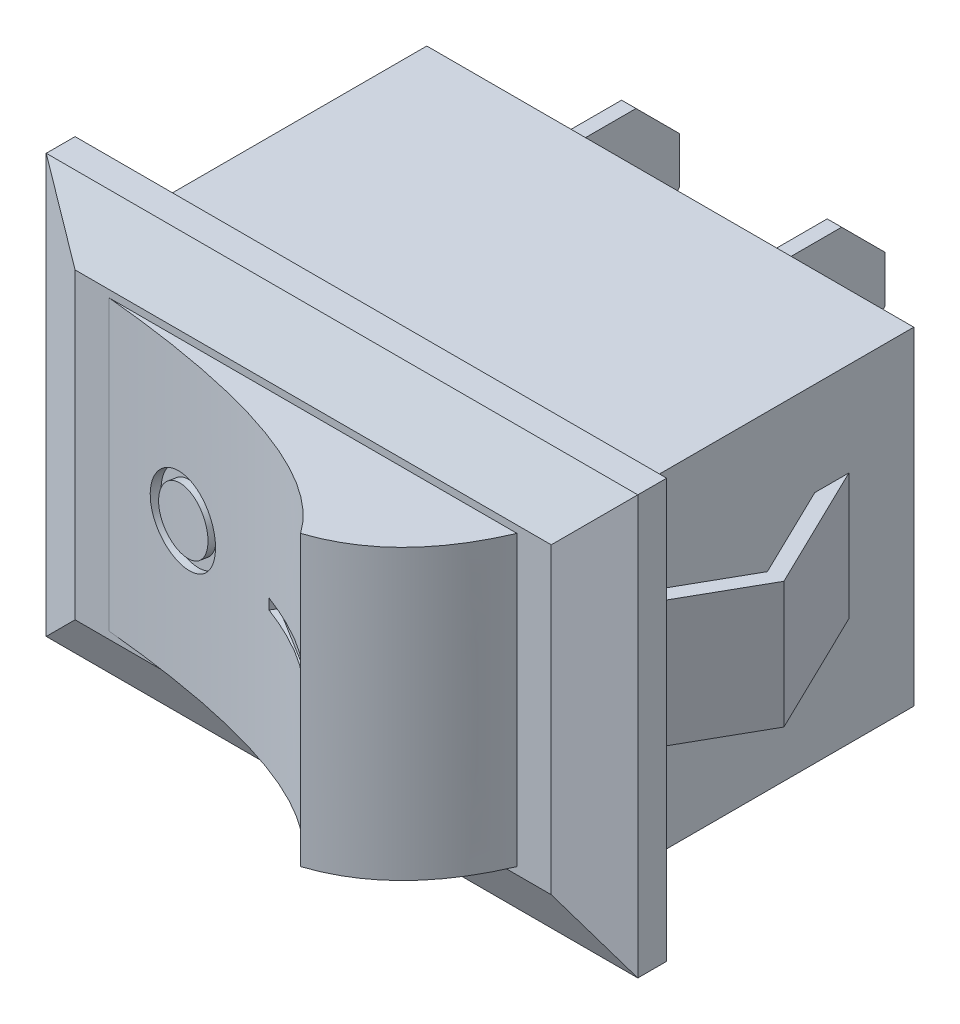
SolidWorks part; units mm, degrees
ref_plane "Front" through (0, 0, 0) normal (0, 0, 1) x (1, 0, 0)
ref_plane "Top" through (0, 0, 0) normal (0, 1, 0) x (1, 0, 0)
ref_plane "Right" through (0, 0, 0) normal (1, 0, 0) x (0, 0, -1)
sketch "Sketch1" plane through (0, 0, 0) normal (0, 0, 1) x (1, 0, 0)
  line L1 (0, 0) -> (17.145, 0)
  line L2 (0, 0) -> (0, 11.557)
  line L3 (0, 11.557) -> (17.145, 11.557)
  line L4 (17.145, 0) -> (17.145, 11.557)
  dimension "D1" = 17.145
  dimension "D2" = 11.557
extrude "Boss-Extrude1" add sketch "Sketch1" along normal blind 10.541
sketch "Sketch2" plane through (0, 0, 0) normal (0, 0, -1) x (-1, 0, 0)
  line L0 (-1.905, 11.557) -> (-1.905, 0) construction
  line L1 (-17.145, 11.557) -> (0, 11.557) construction
  line L2 (0, 0) -> (-17.145, 0) construction
  line L3 (-9.144, 11.557) -> (-9.144, 0) construction
  line L4 (0, 5.7785) -> (-17.145, 5.7785) construction
  line L5 (0, 11.557) -> (0, 0) construction
  line L6 (-17.145, 0) -> (-17.145, 11.557) construction
  line L8 (-2.159, 3.429) -> (-1.651, 3.429)
  line L9 (-2.159, 3.429) -> (-2.159, 8.128)
  line L10 (-2.159, 8.128) -> (-1.651, 8.128)
  line L11 (-1.651, 3.429) -> (-1.651, 8.128)
  line L12 (-2.159, 3.429) -> (-1.651, 8.128) construction
  line L13 (-2.159, 8.128) -> (-1.651, 3.429) construction
  line L14 (-9.398, 3.429) -> (-8.89, 3.429)
  line L15 (-9.398, 3.429) -> (-9.398, 8.128)
  line L16 (-9.398, 8.128) -> (-8.89, 8.128)
  line L17 (-8.89, 3.429) -> (-8.89, 8.128)
  line L18 (-9.398, 3.429) -> (-8.89, 8.128) construction
  line L19 (-9.398, 8.128) -> (-8.89, 3.429) construction
  point P14 (-1.905, 5.7785)
  point P19 (-9.144, 5.7785)
  dimension "D1" = 1.905
  dimension "D2" = 9.144
  dimension "D3" = 0.508
  dimension "D4" = 4.699
extrude "Boss-Extrude2" add sketch "Sketch2" along normal blind 6.731
sketch "Sketch3" plane through (1.651, 0, 0) normal (-1, 0, 0) x (0, 0, 1)
  line L0 (-4.191, 8.128) -> (-4.191, 3.429) construction
  line L1 (-6.731, 8.128) -> (0, 8.128) construction
  line L2 (-6.731, 3.429) -> (0, 3.429) construction
  line L3 (-6.731, 5.7785) -> (0, 5.7785) construction
  line L4 (-6.731, 3.429) -> (-6.731, 8.128) construction
  line L5 (0, 3.429) -> (0, 8.128) construction
  line L6 (-6.731, 6.604) -> (-5.207, 8.128)
  line L7 (-5.207, 8.128) -> (-6.731, 8.128)
  line L8 (-6.731, 8.128) -> (-6.731, 6.604)
  line L9 (-6.731, 4.953) -> (-5.207, 3.429)
  line L10 (-5.207, 3.429) -> (-6.731, 3.429)
  line L11 (-6.731, 3.429) -> (-6.731, 4.953)
  arc A0 (-4.699, 5.3975) -> (-4.699, 6.1595) centre (-4.191, 5.7785) ccw
  circle A1 centre (-0.508, 5.7785) radius 0.381
  arc A2 (-4.699, 6.1595) -> (-4.699, 5.3975) centre (-4.699, 5.7785) ccw
  dimension "D2" = 1.27
  dimension "D7" = 0.762
  dimension "D9" = 0.762
  dimension "D1" = 2.54
  dimension "D3" = 1.524
  dimension "D4" = 1.524
  dimension "D5" = 1.524
  dimension "D6" = 1.524
  dimension "D8" = 0.508
  dimension "D10" = 0.508
extrude "Cut-Extrude1" cut sketch "Sketch3" against normal up to surface (7.747 mm away) up to face at (9.398, 5.7785, -3.3655)
sketch "Sketch4" plane through (0, 0, 10.541) normal (0, 0, 1) x (1, 0, 0)
  line L0 (0, 5.7785) -> (17.145, 5.7785) construction
  line L1 (0, 11.557) -> (0, 0) construction
  line L2 (17.145, 0) -> (17.145, 11.557) construction
  line L3 (8.5725, 11.557) -> (8.5725, 0) construction
  line L4 (17.145, 11.557) -> (0, 11.557) construction
  line L5 (0, 0) -> (17.145, 0) construction
  line L7 (-1.8415, -1.5875) -> (18.9865, -1.5875)
  line L8 (-1.8415, -1.5875) -> (-1.8415, 13.1445)
  line L9 (-1.8415, 13.1445) -> (18.9865, 13.1445)
  line L10 (18.9865, -1.5875) -> (18.9865, 13.1445)
  line L11 (-1.8415, -1.5875) -> (18.9865, 13.1445) construction
  line L12 (-1.8415, 13.1445) -> (18.9865, -1.5875) construction
  line L13 (1.3904, 0.6985) -> (15.7546, 0.6985)
  line L14 (1.3904, 0.6985) -> (1.3904, 10.8585)
  line L15 (1.3904, 10.8585) -> (15.7546, 10.8585)
  line L16 (15.7546, 0.6985) -> (15.7546, 10.8585)
  line L17 (1.3904, 0.6985) -> (15.7546, 10.8585) construction
  line L18 (1.3904, 10.8585) -> (15.7546, 0.6985) construction
  point P12 (8.5725, 5.7785)
  point P18 (8.5725, 5.7785)
  dimension "D1" = 14.732
  dimension "D2" = 20.828
  dimension "D3" = 2.286
extrude "Boss-Extrude3" add sketch "Sketch4" along normal blind 2.032
sketch "Sketch5" plane through (0, -1.5875, 0) normal (0, -1, 0) x (1, 0, 0)
  line L0 (-1.8415, 11.557) -> (0.1905, 12.573)
  line L1 (-1.8415, 12.573) -> (-1.8415, 10.541) construction
  line L2 (-1.8415, 12.573) -> (18.9865, 12.573) construction
  line L3 (0.1905, 12.573) -> (-1.8415, 12.573)
  line L4 (-1.8415, 12.573) -> (-1.8415, 11.557)
  line L5 (16.9545, 12.573) -> (18.9865, 11.557)
  line L6 (18.9865, 12.573) -> (18.9865, 10.541) construction
  line L7 (18.9865, 11.557) -> (18.9865, 12.573)
  line L8 (18.9865, 12.573) -> (16.9545, 12.573)
  dimension "D1" = 2.032
  dimension "D2" = 2.032
extrude "Cut-Extrude2" cut sketch "Sketch5" against normal through all
sketch "Sketch6" plane through (18.9865, 0, 0) normal (1, 0, 0) x (0, 0, -1)
  line L0 (-11.557, 13.1445) -> (-12.573, 11.1125)
  line L1 (-12.573, 13.1445) -> (-12.573, -1.5875) construction
  line L2 (-12.573, 11.1125) -> (-12.573, 13.1445)
  line L3 (-12.573, 13.1445) -> (-11.557, 13.1445)
  line L4 (-11.557, -1.5875) -> (-12.573, -1.5875)
  line L5 (-12.573, -1.5875) -> (-12.573, 0.4445)
  line L6 (-12.573, 0.4445) -> (-11.557, -1.5875)
  dimension "D1" = 2.032
  dimension "D2" = 2.032
extrude "Cut-Extrude3" cut sketch "Sketch6" against normal through all
sketch "Sketch7" plane through (0, 10.8585, 0) normal (0, -1, 0) x (1, 0, 0)
  line L0 (15.7492, 10.541) -> (15.7492, 12.573)
  line L1 (17.145, 10.541) -> (0, 10.541) construction
  line L2 (0.1905, 12.573) -> (16.9545, 12.573) construction
  line L3 (15.7492, 10.541) -> (1.3904, 10.541)
  line L4 (18.9865, 10.541) -> (-1.8415, 10.541) construction
  line L5 (1.3904, 10.541) -> (1.3904, 12.573)
  line L8 (19.7493, 16.383) -> (0.1105, 16.383) construction
  line L9 (11.9392, 16.383) -> (11.9392, 12.573) construction
  line L11 (13.7685, 17.517) -> (6.3705, 12.9308) construction
  line L12 (1.3904, 12.573) -> (11.6865, 14.6092) construction
  line L13 (15.7546, 12.573) -> (1.3904, 12.573) construction
  spline S0 degree 2 poles (15.7492, 12.573) (14.4766, 15.554) (11.9392, 16.383) knots 0 0 0 1 1 1
  spline S1 degree 2 poles (11.9392, 16.383) (9.8247, 13.3881) (1.3904, 12.573) knots 0 0 0 1 1 1
  dimension "D3" = 3.81
  dimension "D4" = 3.81
extrude "Boss-Extrude4" add sketch "Sketch7" along normal up to surface (10.16 mm away) up to face at (8.5725, 0.6985, 11.557)
ref_plane "Plane1" through (-4.0221, 0, 6.4881) normal (0.5269, 0, -0.8499) x (-0.8499, 0, -0.5269)
sketch "Sketch8" plane through (-4.0221, 0, 6.4881) normal (0.5269, 0, -0.8499) x (-0.8499, 0, -0.5269)
  line L0 (-18.7796, 5.7785) -> (-6.7866, 5.7785) construction
  line L1 (-17.6233, 5.9638) -> (-14.5679, 5.9638)
  line L2 (-17.6233, 5.9638) -> (-17.6233, 5.5932)
  line L3 (-17.6233, 5.5932) -> (-14.5679, 5.5932)
  line L4 (-14.5679, 5.9638) -> (-14.5679, 5.5932)
  line L5 (-17.6233, 5.9638) -> (-14.5679, 5.5932) construction
  line L6 (-17.6233, 5.5932) -> (-14.5679, 5.9638) construction
  line L7 (-18.7796, 0.6985) -> (-18.7796, 10.8585) construction
  line L8 (-6.7866, 11.1125) -> (-6.7866, 0.4445) construction
  point P0 (-16.0956, 5.7785)
extrude "Cut-Extrude4" cut sketch "Sketch8" along normal blind 0.4445
ref_plane "Plane2" through (-2.3406, 0, 11.8351) normal (-0.194, 0, 0.981) x (0.981, 0, 0.194)
sketch "Sketch9" plane through (-2.3406, 0, 11.8351) normal (-0.194, 0, 0.981) x (0.981, 0, 0.194)
  line L0 (14.8908, 5.7785) -> (3.6653, 5.7785) construction
  circle A0 centre (6.8497, 5.7785) radius 1.4104
  circle A1 centre (6.8497, 5.7785) radius 1.0663
extrude "Cut-Extrude5" cut sketch "Sketch9" against normal blind 0.4572
ref_plane "Plane3" through (0, 8.255, 0) normal (0, 1, 0) x (1, 0, 0)
sketch "Sketch10" plane through (0, 8.255, 0) normal (0, 1, 0) x (1, 0, 0)
  line L0 (-2.159, -6.731) -> (8.5725, -6.731) construction
  line L1 (8.5725, 0) -> (8.5725, -10.541) construction
  line L2 (0, 0) -> (17.145, 0) construction
  line L3 (-1.8415, -10.541) -> (18.9865, -10.541) construction
  line L4 (0, -10.541) -> (0, 0) construction
  line L5 (0, -10.541) -> (17.145, -10.541) construction
  line L6 (0, -10.541) -> (-2.159, -6.731)
  line L7 (-2.159, -6.731) -> (0, -2.286)
  line L8 (0, -2.286) -> (0, -3.4881)
  line L9 (0, -3.4881) -> (-1.5751, -6.731)
  line L10 (-1.5751, -6.731) -> (0, -9.5106)
  line L11 (0, -9.5106) -> (0, -10.541)
  dimension "D1" = 2.159
  dimension "D2" = 3.81
  dimension "D3" = 0.508
  dimension "D4" = 2.286
extrude "Boss-Extrude5" add sketch "Sketch10" against normal offset from surface (4.445 mm away) 3.81 up to face at (8.5725, 0, 5.2705)
ref_plane "Plane4" through (8.5725, 0, 0) normal (1, 0, 0) x (0, 0, 1)
mirror "Mirror1" about plane through (8.5725, 0, 0) normal (1, 0, 0) of "Boss-Extrude5"
